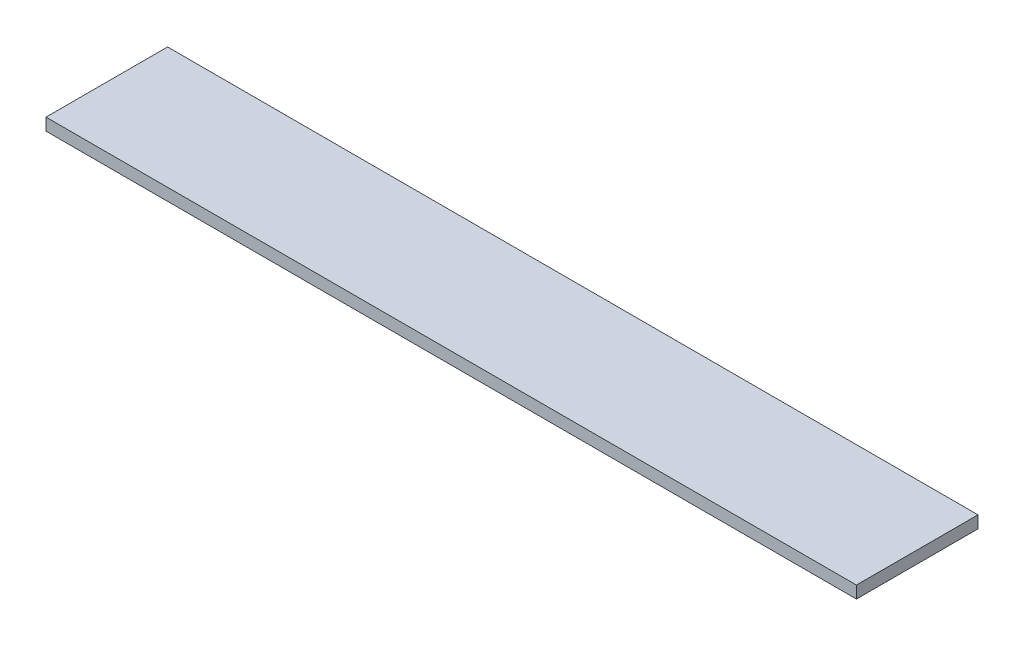
SolidWorks part; units mm, degrees
ref_plane "Front Plane" through (0, 0, 0) normal (0, 0, 1) x (1, 0, 0)
ref_plane "Top Plane" through (0, 0, 0) normal (0, 1, 0) x (1, 0, 0)
ref_plane "Right Plane" through (0, 0, 0) normal (1, 0, 0) x (0, 0, -1)
sketch "Sketch1" plane through (0, 0, 0) normal (0, 1, 0) x (1, 0, 0)
  line L1 (-71.7878, -1.5475) -> (128.2122, -1.5475)
  line L2 (-71.7878, -1.5475) -> (-71.7878, 28.4525)
  line L3 (-71.7878, 28.4525) -> (128.2122, 28.4525)
  line L4 (128.2122, -1.5475) -> (128.2122, 28.4525)
  dimension "D1" = 200
  dimension "D2" = 30
extrude "Boss-Extrude1" add sketch "Sketch1" along normal blind 3
